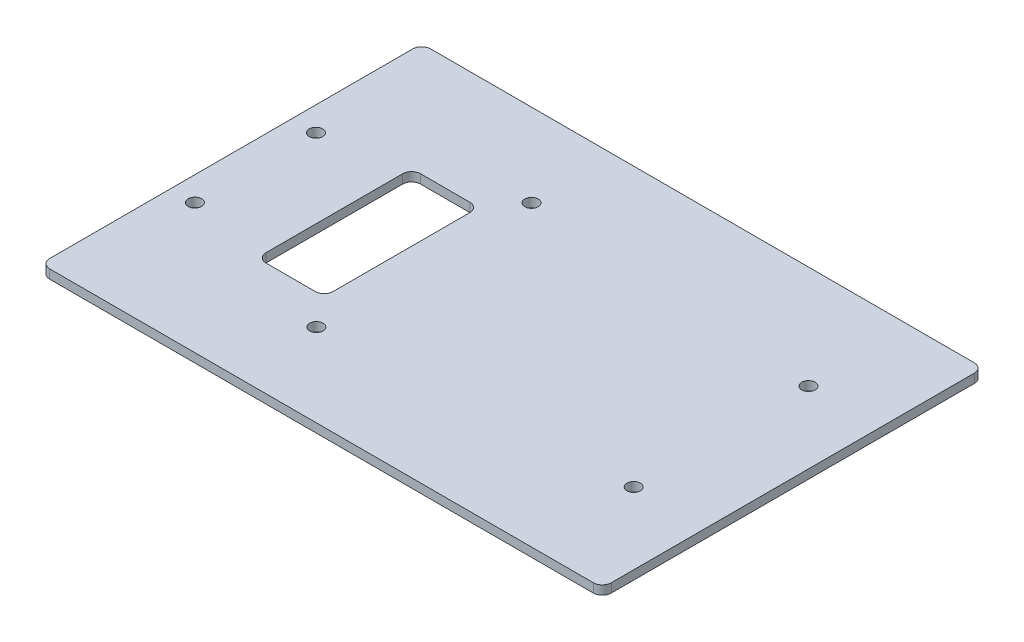
SolidWorks part; units mm, degrees
ref_plane "前视基准面" through (0, 0, 0) normal (0, 0, 1) x (1, 0, 0)
ref_plane "上视基准面" through (0, 0, 0) normal (0, 1, 0) x (1, 0, 0)
ref_plane "右视基准面" through (0, 0, 0) normal (1, 0, 0) x (0, 0, -1)
other "Configuration Table"
sketch "草图1" plane through (0, 0, 0) normal (0, 1, 0) x (1, 0, 0)
  line L0 (-39.65, 52.2066) -> (-39.65, -53.2156) construction
  line L1 (-62.65, -42.5) -> (62.65, -42.5)
  line L2 (-62.65, -42.5) -> (-62.65, 42.5)
  line L3 (-62.65, 42.5) -> (62.65, 42.5)
  line L4 (62.65, -42.5) -> (62.65, 42.5)
  line L5 (-62.65, -42.5) -> (62.65, 42.5) construction
  line L6 (-62.65, 42.5) -> (62.65, -42.5) construction
  line L7 (-1000, 0) -> (49000, 0) construction
  line L8 (46.65, 52.2199) -> (46.65, -52.2174) construction
  line L9 (-39.65, -17.25) -> (-24.65, -17.25)
  line L10 (-39.65, -17.25) -> (-39.65, 17.25)
  line L11 (-39.65, 17.25) -> (-24.65, 17.25)
  line L12 (-24.65, -17.25) -> (-24.65, 17.25)
  circle A0 centre (-19.65, 24) radius 1.5
  circle A1 centre (-19.65, -24) radius 1.5
  circle A2 centre (46.65, 19.5) radius 1.5
  circle A3 centre (46.65, -19.5) radius 1.5
  point P0 (0, 0)
  dimension "D6" = 3
  dimension "D8" = 48
  dimension "D9" = 3
  dimension "D10" = 39
  dimension "D1" = 125.3
  dimension "D2" = 85
  dimension "D3" = 23
  dimension "D4" = 15
  dimension "D5" = 34.5
  dimension "D7" = 43
  dimension "18.5" = 18.5
  dimension "16" = 16
  dimension "23" = 23
extrude "凸台-拉伸1" add sketch "草图1" along normal blind 2
fillet "圆角1" radius 2 8 edges at (-39.65, 1, 17.25) (-24.65, 1, 17.25) (-39.65, 1, -17.25) (-24.65, 1, -17.25) (-62.65, 1, -42.5) (-62.65, 1, 42.5) (62.65, 1, -42.5) (62.65, 1, 42.5)
sketch "草图2" plane through (0, 0, 0) normal (0, -1, 0) x (1, 0, 0)
  line L0 (0, 0) -> (98.2919, 0) construction
  line L1 (-62.65, -40.5) -> (-62.65, 40.5) construction
  circle A0 centre (-57.25, -13.5) radius 1.5
  circle A1 centre (-57.25, 13.5) radius 1.5
  point P2 (-53.0023, -11.3255)
  point P7 (0, 0)
  point P9 (-66.4389, -15.6008)
  dimension "D1" = 3
  dimension "D2" = 27
  dimension "D3" = 5.4
extrude "切除-拉伸2" cut sketch "草图2" against normal up to next
